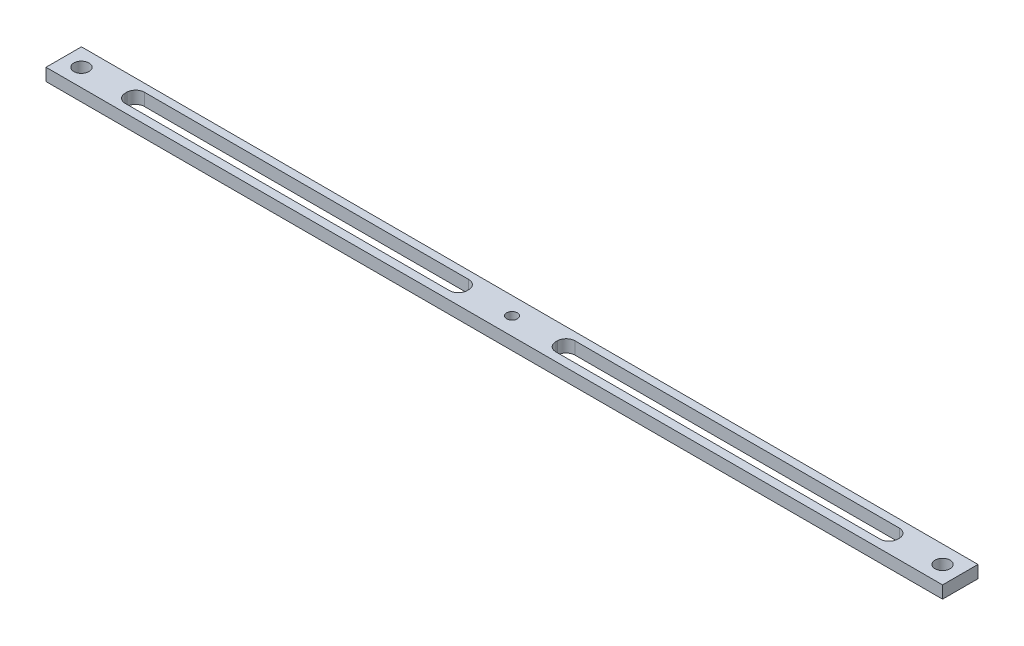
SolidWorks part; units mm, degrees
ref_plane "Płaszczyzna przednia" through (0, 0, 0) normal (0, 0, 1) x (1, 0, 0)
ref_plane "Płaszczyzna górna" through (0, 0, 0) normal (0, 1, 0) x (1, 0, 0)
ref_plane "Płaszczyzna prawa" through (0, 0, 0) normal (1, 0, 0) x (0, 0, -1)
sketch "Szkic1" plane through (0, 0, 0) normal (0, 1, 0) x (1, 0, 0)
  line L0 (253, 0) -> (253, 10)
  line L1 (0, 0) -> (506, 0)
  line L2 (0, 0) -> (0, 20)
  line L3 (0, 20) -> (506, 20)
  line L4 (506, 0) -> (506, 20)
  line L5 (0, 10) -> (10, 10)
  line L6 (506, 10) -> (496, 10)
  line L8 (40, 15.5746) -> (223, 15.5746)
  line L9 (35, 10.5746) -> (35, 9.6967)
  line L10 (40, 4.6967) -> (223, 4.6967)
  line L11 (228, 10.5746) -> (228, 9.6967)
  line L12 (283, 15.5746) -> (466, 15.5746)
  line L13 (278, 10.5746) -> (278, 9.7528)
  line L14 (283, 4.7528) -> (466, 4.7528)
  line L15 (471, 10.5746) -> (471, 9.7528)
  circle A0 centre (253, 10) radius 3
  circle A1 centre (10, 10) radius 4.25
  circle A2 centre (496, 10) radius 4.25
  arc A3 (466, 4.7528) -> (471, 9.7528) centre (466, 9.7528) ccw
  arc A4 (471, 10.5746) -> (466, 15.5746) centre (466, 10.5746) ccw
  arc A5 (283, 4.7528) -> (278, 9.7528) centre (283, 9.7528) cw
  arc A6 (283, 15.5746) -> (278, 10.5746) centre (283, 10.5746) ccw
  arc A7 (35, 9.6967) -> (40, 4.6967) centre (40, 9.6967) ccw
  arc A8 (223, 4.6967) -> (228, 9.6967) centre (223, 9.6967) ccw
  arc A9 (228, 10.5746) -> (223, 15.5746) centre (223, 10.5746) ccw
  arc A10 (40, 15.5746) -> (35, 10.5746) centre (40, 10.5746) ccw
  dimension "D1" = 5
  dimension "D2" = 20
  dimension "D6" = 8.5
  dimension "D7" = 6
  dimension "D8" = 8.5
  dimension "D11" = 35
  dimension "D3" = 506
  dimension "D4" = 183
  dimension "D5" = 183
  dimension "D9" = 10
  dimension "D10" = 10
  dimension "D12" = 35
extrude "Dodanie-wyciągnięcie1" add sketch "Szkic1" along normal blind 7
